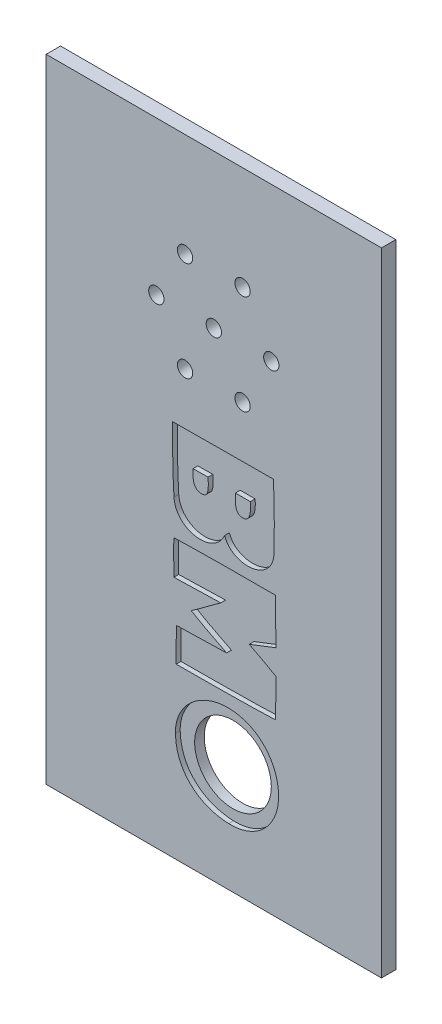
SolidWorks part; units mm, degrees
ref_plane "Front Plane" through (0, 0, 0) normal (0, 0, 1) x (1, 0, 0)
ref_plane "Top Plane" through (0, 0, 0) normal (0, 1, 0) x (1, 0, 0)
ref_plane "Right Plane" through (0, 0, 0) normal (1, 0, 0) x (0, 0, -1)
sketch "Sketch1" plane through (0, 0, 0) normal (0, 0, 1) x (1, 0, 0)
  line L1 (-35, -66) -> (35, -66)
  line L2 (-35, -66) -> (-35, 66)
  line L3 (-35, 66) -> (35, 66)
  line L4 (35, -66) -> (35, 66)
  line L5 (-35, -66) -> (35, 66) construction
  line L6 (-35, 66) -> (35, -66) construction
  point P0 (0, 0)
  dimension "D1" = 70
  dimension "D2" = 132
extrude "Boss-Extrude1" add sketch "Sketch1" along normal blind 3
sketch "Sketch2" plane through (0, 0, 3) normal (0, 0, 1) x (1, 0, 0)
  line L0 (35, 66) -> (-35, 66) construction
  line L1 (35, -66) -> (35, 66) construction
  line L2 (35, 66) -> (-35, 66) construction
  circle A0 centre (0, 34) radius 1.6
  circle A1 centre (12, 34) radius 1.6
  circle A2 centre (6, 23.6077) radius 1.6
  circle A3 centre (-6, 23.6077) radius 1.6
  circle A4 centre (-12, 34) radius 1.6
  circle A5 centre (-6, 44.3923) radius 1.6
  circle A6 centre (6, 44.3923) radius 1.6
  circle A7 centre (3, -43.8976) radius 8
  point P2 (0, 66)
  point P24 (0, 34)
  dimension "D1" = 3.2
  dimension "D6" = 3.2
  dimension "D11" = 16
  dimension "D12" = 32
  dimension "D2" = 32
  dimension "D3" = 35
  dimension "D4" = 12
  dimension "D5" = 32
  dimension "D8" = 12
  dimension "D9" = 12
  dimension "D10" = 44
  dimension "D7" = 6
extrude "Cut-Extrude1" cut sketch "Sketch2" against normal through all
sketch "Sketch4" plane through (0, 0, 3) normal (0, 0, 1) x (1, 0, 0)
  line L0 (12.4354, 12.9067) -> (-8.5913, 12.7905)
  line L1 (-4.3265, 6.4259) -> (-1.2067, 6.4556)
  line L2 (4.5213, 6.4386) -> (7.6195, 6.4377)
  spline S0 degree 3 poles (3.3668, -33.1601) (9.4177, -33.3928) (13.4451, -38.0575) (13.5295, -43.7482) (13.614, -49.4416) (9.143, -54.2627) (3.092, -54.03) knots 2 2 2 2 3 3 3 4 4 4 4
  spline S1 degree 3 poles (-8.0183, -43.2933) (-8.1332, -37.5976) (-2.6869, -32.9274) (3.3668, -33.1601) knots 1 1 1 1 2 2 2 2
  spline S2 degree 3 poles (3.092, -54.03) (-2.9617, -53.7945) (-7.8833, -49.9783) (-8.0183, -43.2933) knots 0 0 0 0 1 1 1 1
  spline S3 degree 3 poles (-8.315, -8.0629) (-4.4062, -7.8974) (8.0681, -7.8226) (12.84, -7.8621) knots 11 11 11 11 12 12 12 12
  spline S4 degree 3 poles (-8.333, -15.2105) (-8.3559, -13.67) (-8.4259, -8.9466) (-8.315, -8.0629) knots 10 10 10 10 11 11 11 11
  spline S5 degree 3 poles (1.4483, -14.9524) (-3.199, -15.1343) (-7.2307, -15.1941) (-8.333, -15.2105) knots 9 9 9 9 10 10 10 10
  spline S6 degree 3 poles (-4.7229, -19.4348) (-2.6645, -18.0895) (0.3558, -15.6274) (1.4483, -14.9524) knots 8 8 8 8 9 9 9 9
  spline S7 degree 3 poles (2.6733, -23.3935) (-0.7754, -21.6861) (-3.7375, -20.0818) (-4.7229, -19.4348) knots 7 7 7 7 8 8 8 8
  spline S8 degree 3 poles (-7.8411, -23.6543) (-4.785, -23.6089) (1.0833, -23.4171) (2.6733, -23.3935) knots 6 6 6 6 7 7 7 7
  spline S9 degree 3 poles (-7.858, -30.6888) (-8.0102, -28.6072) (-7.7051, -24.6473) (-7.8411, -23.6543) knots 5 5 5 5 6 6 6 6
  spline S10 degree 3 poles (12.926, -30.3804) (7.7953, -30.6771) (-6.3892, -30.667) (-7.858, -30.6888) knots 4 4 4 4 5 5 5 5
  spline S11 degree 3 poles (12.9355, -22.4722) (12.9779, -25.33) (12.9097, -29.2836) (12.926, -30.3804) knots 3 3 3 3 4 4 4 4
  spline S12 degree 3 poles (7.3838, -19.4785) (9.1082, -20.3322) (12.3145, -22.0459) (12.9355, -22.4722) knots 2 2 2 2 3 3 3 3
  spline S13 degree 3 poles (12.9802, -17.3116) (11.7631, -17.7652) (8.1147, -19.1369) (7.3838, -19.4785) knots 1 1 1 1 2 2 2 2
  spline S14 degree 3 poles (12.84, -7.8621) (12.8612, -9.2951) (12.959, -15.8814) (12.9802, -17.3116) knots 0 0 0 0 1 1 1 1
  spline S15 degree 3 poles (2.262, -2.3574) (3.6475, -6.9373) (12.3287, -6.6541) (12.5772, -0.3714) knots 0 0 0 0 1 1 1 1
  spline S16 degree 3 poles (12.5772, -0.3714) (12.6572, 1.6695) (12.6541, 9.685) (12.4354, 12.9067) knots 1 1 1 1 2 2 2 2
  spline S17 degree 3 poles (-8.5913, 12.7905) (-8.7043, 8.8858) (-8.5026, 1.7938) (-8.325, -0.7008) knots 3 3 3 3 4 4 4 4
  spline S18 degree 3 poles (-8.325, -0.7008) (-7.9278, -6.2931) (-0.0516, -7.4938) (2.262, -2.3574) knots 4 4 4 4 5 5 5 5
  spline S19 degree 3 poles (-1.2067, 6.4556) (-1.074, 4.5722) (-1.0153, 2.8421) (-2.4199, 2.7661) knots 1 1 1 1 2 2 2 2
  spline S20 degree 3 poles (-2.4199, 2.7661) (-3.9733, 2.6824) (-4.4937, 3.9482) (-4.3265, 6.4259) knots 2 2 2 2 3 3 3 3
  spline S21 degree 3 poles (7.6195, 6.4377) (7.7549, 4.5571) (7.5909, 2.7879) (6.1863, 2.7119) knots 1 1 1 1 2 2 2 2
  spline S22 degree 3 poles (6.1863, 2.7119) (4.6357, 2.631) (4.3513, 3.9636) (4.5213, 6.4386) knots 2 2 2 2 3 3 3 3
extrude "Cut-Extrude4" cut sketch "Sketch4" against normal blind 1
